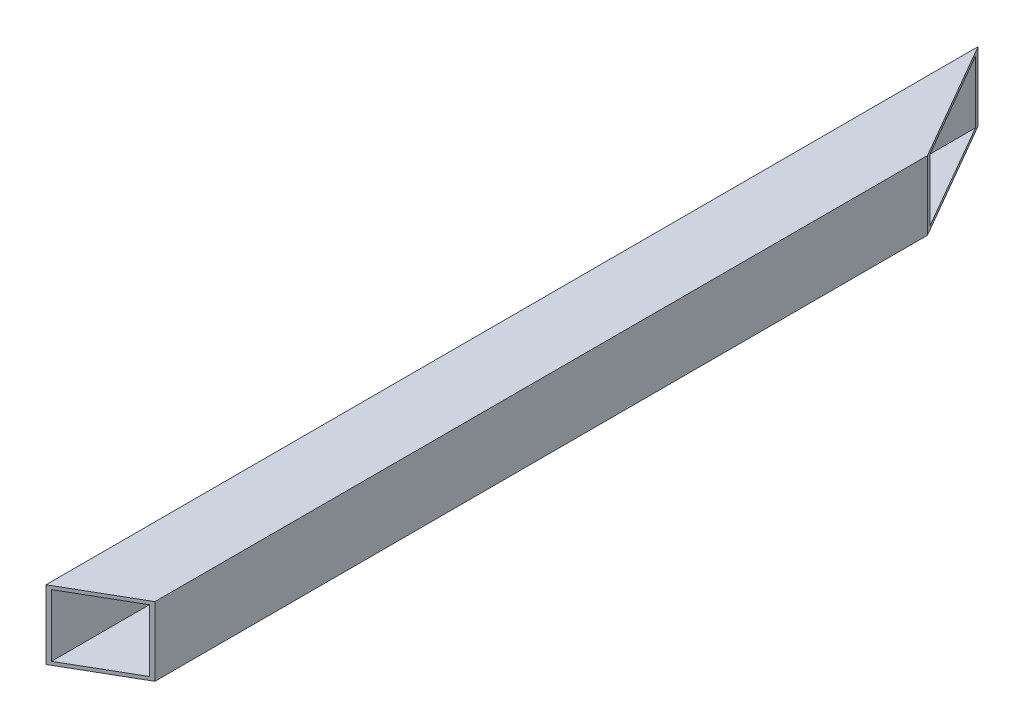
SolidWorks part; units mm, degrees
material "1100-H12 棒材(SS)"
ref_plane "前视基准面" through (0, 0, 0) normal (0, 0, 1) x (1, 0, 0)
ref_plane "上视基准面" through (0, 0, 0) normal (0, 1, 0) x (1, 0, 0)
ref_plane "右视基准面" through (0, 0, 0) normal (1, 0, 0) x (0, 0, -1)
other "Configuration Table"
sketch "草图1" plane through (0, 0, 0) normal (0, 0, 1) x (1, 0, 0)
  line L1 (0, 0) -> (20, 0)
  line L2 (0, 0) -> (0, 20)
  line L3 (0, 20) -> (20, 20)
  line L4 (20, 0) -> (20, 20)
  line L5 (1, 1) -> (19, 1)
  line L6 (1, 1) -> (1, 19)
  line L7 (1, 19) -> (19, 19)
  line L8 (19, 1) -> (19, 19)
  dimension "D1" = 20
  dimension "D2" = 20
  dimension "D3" = 1
  dimension "D4" = 1
  dimension "D5" = 1
  dimension "D6" = 1
extrude "凸台-拉伸1" add sketch "草图1" along normal blind 270
sketch "草图2" plane through (0, 20, 0) normal (0, 1, 0) x (1, 0, 0)
  line L0 (0, 0) -> (20, 0)
  line L1 (20, 0) -> (20, -34.641)
  line L2 (20, -270) -> (20, 0) construction
  line L3 (20, -34.641) -> (0, 0)
  line L4 (0, -270) -> (20, -258.453)
  line L5 (20, -258.453) -> (20, -270)
  line L6 (20, -270) -> (0, -270)
  dimension "D1" = 60
extrude "切除-拉伸1" cut sketch "草图2" against normal blind 120
